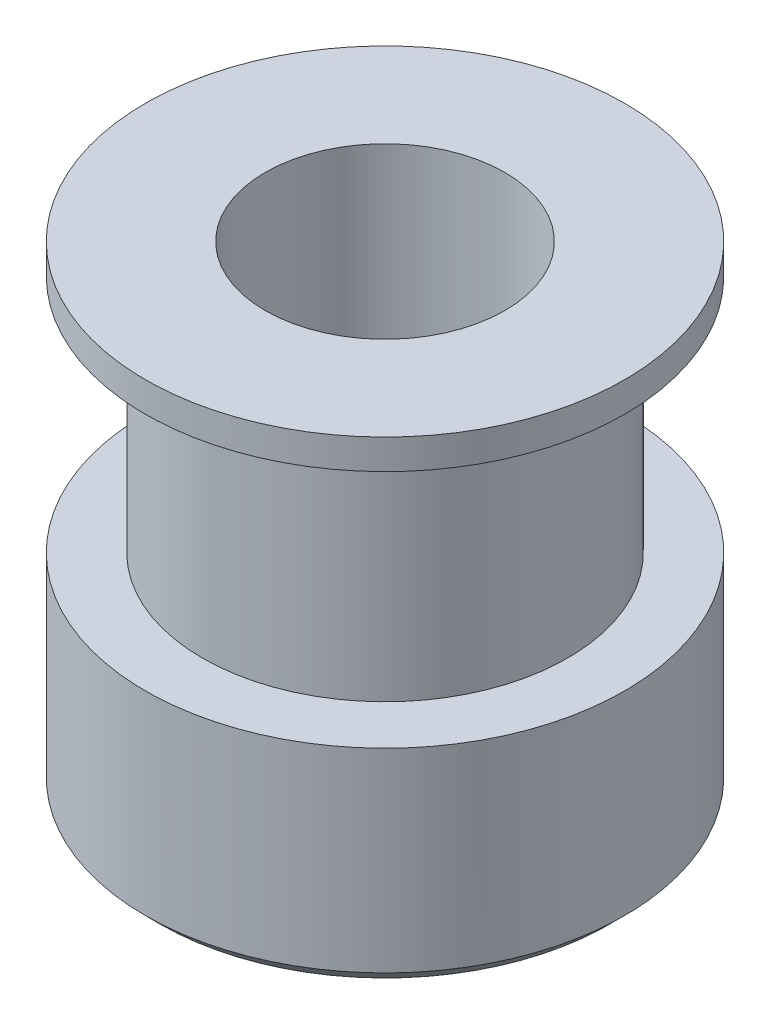
SolidWorks part; units mm, degrees
ref_plane "Front Plane" through (0, 0, 0) normal (0, 0, 1) x (1, 0, 0)
ref_plane "Top Plane" through (0, 0, 0) normal (0, 1, 0) x (1, 0, 0)
ref_plane "Right Plane" through (0, 0, 0) normal (1, 0, 0) x (0, 0, -1)
sketch "Sketch1" plane through (0, 0, 0) normal (0, 0, 1) x (1, 0, 0)
  line L0 (-4, 0) -> (-4, 16)
  line L1 (-4, 16) -> (-8, 16)
  line L2 (-8, 16) -> (-8, 15)
  line L3 (-8, 15) -> (-6.1, 15)
  line L4 (-6.1, 15) -> (-6.1, 7)
  line L5 (-6.1, 7) -> (-8, 7)
  line L8 (-8, 7) -> (-8, 0)
  line L9 (-8, 0) -> (-4, 0)
  line L10 (0, 0) -> (0, 23.1903) construction
  line L11 (0, 0) -> (-4.875, 0) construction
  dimension "D1" = 16
  dimension "D2" = 8
  dimension "D3" = 12.2
  dimension "D4" = 16
  dimension "D5" = 16
  dimension "D6" = 1
  dimension "D7" = 7
revolve "Revolve1" add sketch "Sketch1" angle 360 about L10
chamfer "Chamfer1" distance 0.5 angle 45 1 edges at (0, 0, -8)
sketch "Sketch2" plane through (0, 0, 0) normal (0, 0, 1) x (1, 0, 0)
  line L0 (0, 7) -> (0, 0) construction
  line L1 (8, 7) -> (-8, 7) construction
  circle A0 centre (0, 3.5) radius 1.5
  dimension "D1" = 3
extrude "Cut-Extrude1" cut sketch "Sketch2" against normal up to next
sketch "Sketch3" plane through (0, 0, 0) normal (1, 0, 0) x (0, 0, -1)
  line L0 (0, 0) -> (0, 7) construction
  line L1 (8, 7) -> (-8, 7) construction
  circle A0 centre (0, 3.5) radius 1.5
  dimension "D1" = 3
extrude "Cut-Extrude2" cut sketch "Sketch3" against normal up to next
